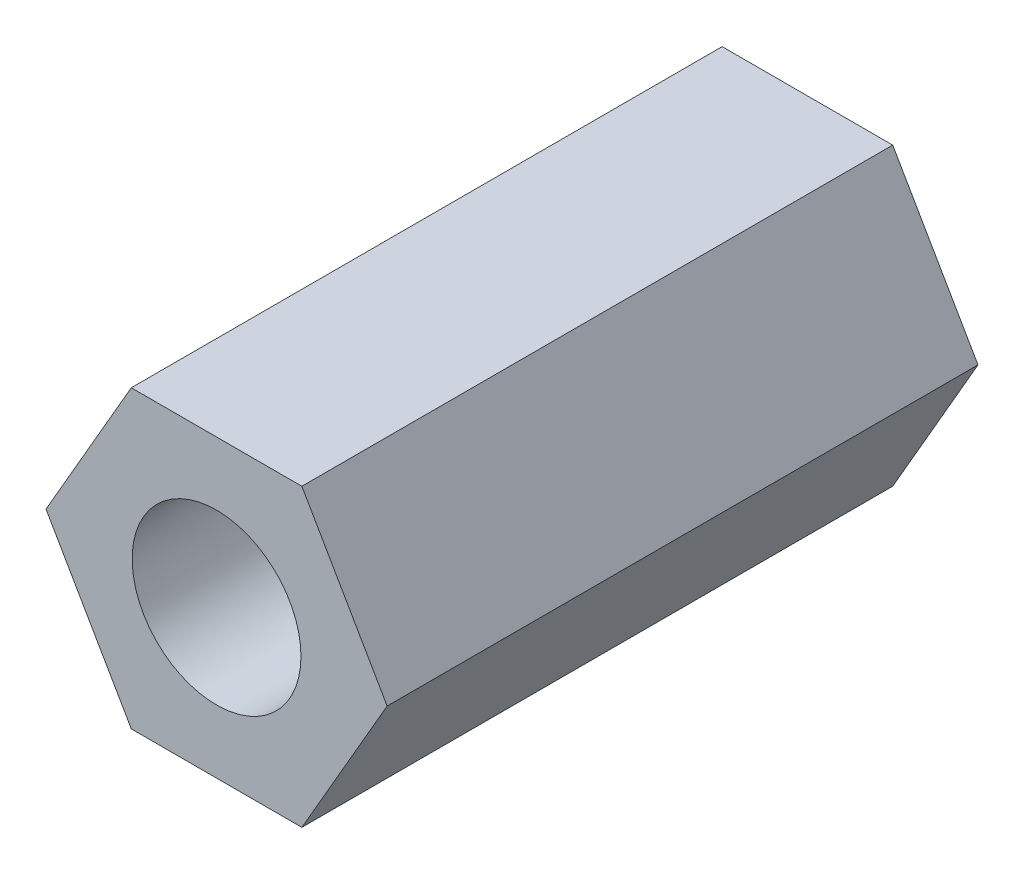
SolidWorks part; units mm, degrees
ref_plane "Piano frontale" through (0, 0, 0) normal (0, 0, 1) x (1, 0, 0)
ref_plane "Piano superiore" through (0, 0, 0) normal (0, 1, 0) x (1, 0, 0)
ref_plane "Piano destro" through (0, 0, 0) normal (1, 0, 0) x (0, 0, -1)
sketch "Schizzo1" plane through (0, 0, 0) normal (0, 0, 1) x (1, 0, 0)
  line L1 (2.0207, 3.5) -> (-2.0207, 3.5)
  line L2 (-2.0207, 3.5) -> (-4.0415, 0)
  line L3 (-4.0415, 0) -> (-2.0207, -3.5)
  line L4 (-2.0207, -3.5) -> (2.0207, -3.5)
  line L5 (2.0207, -3.5) -> (4.0415, 0)
  line L6 (4.0415, 0) -> (2.0207, 3.5)
  circle A0 centre (0, 0) radius 3.5 construction
  dimension "D1" = 7
extrude "Estrusione-Estrusione1" add sketch "Schizzo1" along normal blind 14
sketch "Schizzo2" plane through (0, 0, 14) normal (0, 0, 1) x (1, 0, 0)
  circle A0 centre (0, 0) radius 2
  dimension "D1" = 4
extrude "Taglio-Estrusione1" cut sketch "Schizzo2" against normal blind 15
